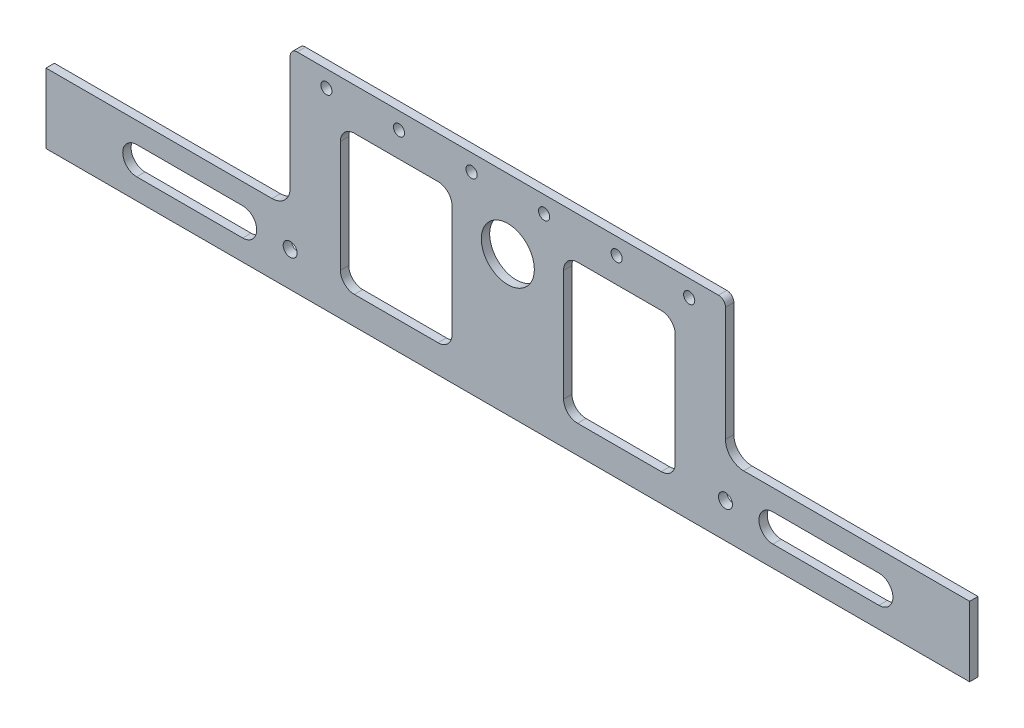
SolidWorks part; units mm, degrees
material "Alumina"
ref_plane "Front Plane" through (0, 0, 0) normal (0, 0, 1) x (1, 0, 0)
ref_plane "Top Plane" through (0, 0, 0) normal (0, 1, 0) x (1, 0, 0)
ref_plane "Right Plane" through (0, 0, 0) normal (1, 0, 0) x (0, 0, -1)
sketch "Sketch1" plane through (0, 0, 0) normal (0, 0, 1) x (1, 0, 0)
  line L0 (0, 0) -> (0, 50000) construction
  line L1 (0, 0) -> (50000, 0) construction
  line L4 (165.5, 0) -> (165.5, 25)
  line L5 (165.5, 25) -> (84.5, 25)
  line L6 (78, 31.5) -> (78, 72.5)
  line L7 (75.5, 75) -> (-75.5, 75)
  line L8 (-78, 72.5) -> (-78, 31.5)
  line L9 (-84.5, 25) -> (-165.5, 25)
  line L10 (-165.5, 25) -> (-165.5, 0)
  line L11 (-165.5, 0) -> (165.5, 0)
  line L12 (-65, 69) -> (-39, 69) construction
  line L13 (-165.5, 12.5) -> (165.5, 12.5) construction
  line L14 (-55, 60) -> (-25, 60)
  line L15 (-60, 55) -> (-60, 15)
  line L16 (-55, 10) -> (-25, 10)
  line L17 (-20, 55) -> (-20, 15)
  line L18 (-133, 12.5) -> (-95, 12.5) construction
  line L19 (-133, 17.5) -> (-95, 17.5)
  line L20 (-133, 7.5) -> (-95, 7.5)
  line L21 (133, 12.5) -> (95, 12.5) construction
  line L22 (133, 17.5) -> (95, 17.5)
  line L23 (133, 7.5) -> (95, 7.5)
  line L24 (55, 10) -> (25, 10)
  line L25 (20, 55) -> (20, 15)
  line L26 (55, 60) -> (25, 60)
  line L27 (60, 55) -> (60, 15)
  arc A0 (-84.5, 25) -> (-78, 31.5) centre (-84.5, 31.5) ccw
  arc A1 (78, 31.5) -> (84.5, 25) centre (84.5, 31.5) ccw
  circle A2 centre (0, 50) radius 9.5
  arc A3 (78, 72.5) -> (75.5, 75) centre (75.5, 72.5) ccw
  arc A4 (-75.5, 75) -> (-78, 72.5) centre (-75.5, 72.5) ccw
  circle A5 centre (-65, 69) radius 2
  circle A6 centre (-39, 69) radius 2
  circle A7 centre (-13, 69) radius 2
  circle A8 centre (13, 69) radius 2
  circle A9 centre (39, 69) radius 2
  circle A10 centre (65, 69) radius 2
  circle A11 centre (-78, 12.5) radius 2.5
  arc A12 (-55, 60) -> (-60, 55) centre (-55, 55) ccw
  arc A13 (-25, 60) -> (-20, 55) centre (-25, 55) cw
  arc A14 (-25, 10) -> (-20, 15) centre (-25, 15) ccw
  arc A15 (-60, 15) -> (-55, 10) centre (-55, 15) ccw
  arc A16 (-133, 17.5) -> (-133, 7.5) centre (-133, 12.5) ccw
  arc A17 (-95, 7.5) -> (-95, 17.5) centre (-95, 12.5) ccw
  arc A26 (133, 17.5) -> (133, 7.5) centre (133, 12.5) cw
  arc A27 (95, 7.5) -> (95, 17.5) centre (95, 12.5) cw
  circle A28 centre (78, 12.5) radius 2.5
  arc A29 (25, 10) -> (20, 15) centre (25, 15) cw
  arc A30 (25, 60) -> (20, 55) centre (25, 55) ccw
  arc A31 (55, 60) -> (60, 55) centre (55, 55) cw
  arc A32 (60, 15) -> (55, 10) centre (55, 15) cw
  point P10 (0, 75)
  point P15 (0, 0)
  point P23 (78, 75)
  point P26 (-78, 75)
  point P59 (-114, 12.5)
  point P86 (114, 12.5)
  dimension "D4" = 13
  dimension "D5" = 19
  dimension "D7" = 2.5
  dimension "D8" = 4
  dimension "D18" = 5
  dimension "D19" = 5
  dimension "D1" = 50
  dimension "156" = 156
  dimension "D2" = 25
  dimension "D3" = 331
  dimension "D6" = 50
  dimension "D9" = 6
  dimension "D10" = 13
  dimension "D12" = 26
  dimension "D13" = 50
  dimension "D14" = 10
  dimension "D15" = 40
  dimension "D16" = 20
  dimension "D17" = 18
  dimension "D20" = 10
  dimension "D21" = 38
  dimension "D22" = 17
  dimension "D11" = 6
extrude "Boss-Extrude1" add sketch "Sketch1" along normal mid plane 3
